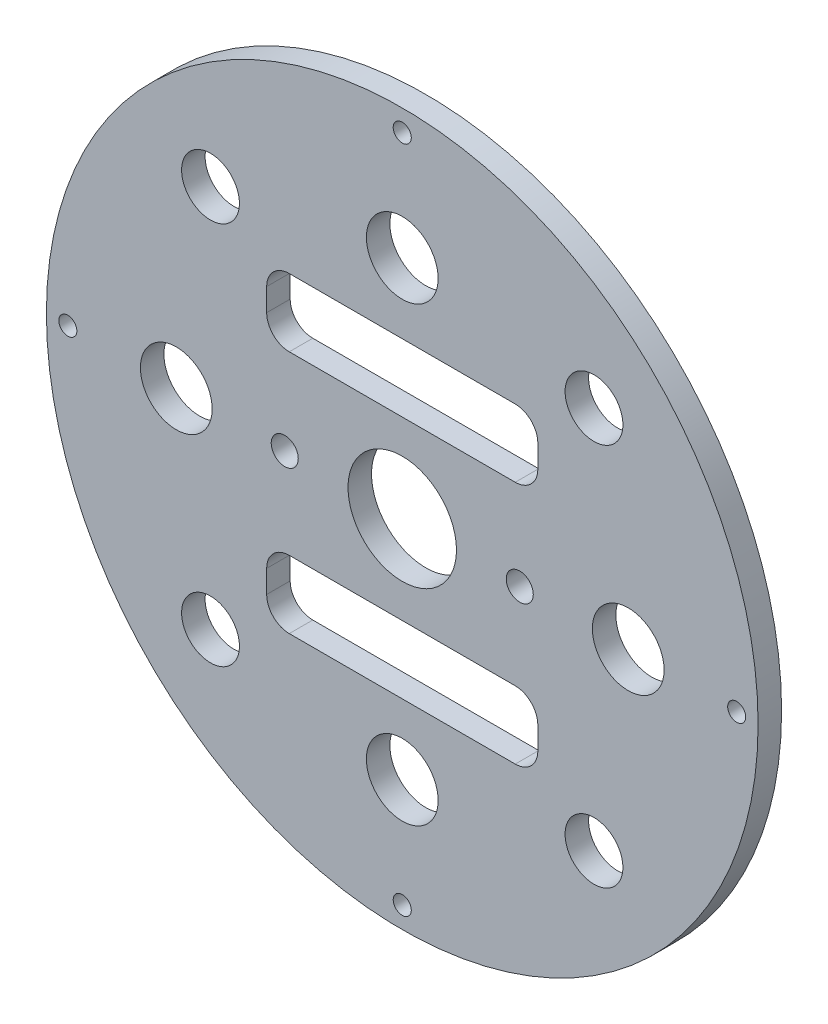
SolidWorks part; units mm, degrees
ref_plane "前视基准面" through (0, 0, 0) normal (0, 0, 1) x (1, 0, 0)
ref_plane "上视基准面" through (0, 0, 0) normal (0, 1, 0) x (1, 0, 0)
ref_plane "右视基准面" through (0, 0, 0) normal (1, 0, 0) x (0, 0, -1)
sketch "草图1" plane through (0, 0, 0) normal (0, 0, 1) x (1, 0, 0)
  circle A0 centre (0, 0) radius 50
  dimension "D1" = 100
extrude "凸台-拉伸1" add sketch "草图1" along normal blind 3.302
sketch "草图2" plane through (0, 0, 3.302) normal (0, 0, 1) x (1, 0, 0)
  line L0 (0, 0) -> (0, 69.5531) construction
  line L1 (0, 0) -> (-26.9408, 26.9408) construction
  line L2 (0, 0) -> (-38.1, 0) construction
  line L3 (0, 0) -> (-26.9408, -26.9408) construction
  circle A0 centre (-26.9408, 26.9408) radius 4.064
  circle A1 centre (-26.9408, -26.9408) radius 4.064
  circle A2 centre (26.9408, -26.9408) radius 4.064
  circle A3 centre (26.9408, 26.9408) radius 4.064
  circle A4 centre (0, 0) radius 38.1 construction
  dimension "D1" = 8.128
  dimension "D2" = 8.128
  dimension "D3" = 45
  dimension "D4" = 8.128
  dimension "D5" = 45
  dimension "D6" = 76.2
extrude "切除-拉伸1" cut sketch "草图2" against normal through all
sketch "草图4" plane through (0, 0, 3.302) normal (0, 0, 1) x (1, 0, 0)
  circle A0 centre (0, 0) radius 7.62
  dimension "D1" = 15.24
extrude "切除-拉伸3" cut sketch "草图4" against normal through all
sketch "草图7" plane through (0, 0, 3.302) normal (0, 0, 1) x (1, 0, 0)
  circle A0 centre (0, 46.99) radius 1.27
  circle A1 centre (46.99, 0) radius 1.27
  circle A2 centre (0, -46.99) radius 1.27
  circle A3 centre (-46.99, 0) radius 1.27
  point P12 (0, 0)
  dimension "D1" = 2.54
  dimension "D2" = 46.99
  dimension "D3" = 4
extrude "切除-拉伸6" cut sketch "草图7" against normal through all
hole_wizard "3/8 Clearance Hole1" positions "Sketch7" profile "Sketch8" hole size "3/8" standard "ANSI Inch" end condition through all
sketch "Sketch7" plane through (0, 0, 3.302) normal (0, 0, 1) x (1, 0, 0)
  circle A0 centre (0, 0) radius 31.75 construction
  point P0 (0, 31.75)
  point P2 (-31.75, 0)
  point P4 (31.75, 0)
  point P6 (0, -31.75)
  dimension "D1" = 63.5
sketch "Sketch8" plane through (0, 31.75, 3.302) normal (1, 0, 0) x (0, -1, 0)
  line L0 (0, 0) -> (0, 3.302)
  line L1 (0, 3.302) -> (5.0419, 3.302)
  line L2 (5.0419, 3.302) -> (5.0419, 0)
  line L5 (5.0419, 0) -> (0, 0)
  line L11 (0, -6.35) -> (0, 107.95) construction
  dimension "Thru Hole Dia." = 10.0838
  dimension "Thru Hole Depth" = 3.302
sketch "Sketch11" plane through (0, 0, 3.302) normal (0, 0, 1) x (1, 0, 0)
  line L0 (0, 0) -> (-11.8931, 0) construction
  line L1 (-16.51, 0) -> (0, 0) construction
  circle A0 centre (-16.51, 0) radius 1.9
  dimension "D1" = 16.51
  dimension "D2" = 3.8
  dimension "D3" = 0
extrude "Cut-Extrude5" cut sketch "Sketch11" against normal through all
pattern_circular "CirPattern1" count 2 over 360 about axis through (0, 0, 0) along (0, 0, 1) of "Cut-Extrude5"
sketch "Sketch12" plane through (0, 0, 3.302) normal (0, 0, 1) x (1, 0, 0)
  line L1 (-19.05, 21.9075) -> (19.05, 21.9075)
  line L2 (-19.05, 21.9075) -> (-19.05, 12.3825)
  line L3 (-19.05, 12.3825) -> (19.05, 12.3825)
  line L4 (19.05, 21.9075) -> (19.05, 12.3825)
  line L5 (-19.05, 21.9075) -> (19.05, 12.3825) construction
  line L6 (-19.05, 12.3825) -> (19.05, 21.9075) construction
  point P0 (0, 17.145)
  dimension "D1" = 17.145
  dimension "D2" = 38.1
  dimension "D3" = 9.525
extrude "Cut-Extrude6" cut sketch "Sketch12" against normal through all
fillet "Fillet1" radius 3.175 4 edges at (19.05, 21.9075, 1.651) (19.05, 12.3825, 1.651) (-19.05, 12.3825, 1.651) (-19.05, 21.9075, 1.651)
mirror "Mirror1" about plane through (0, 0, 0) normal (0, 1, 0) of "Fillet1", "Cut-Extrude6"
